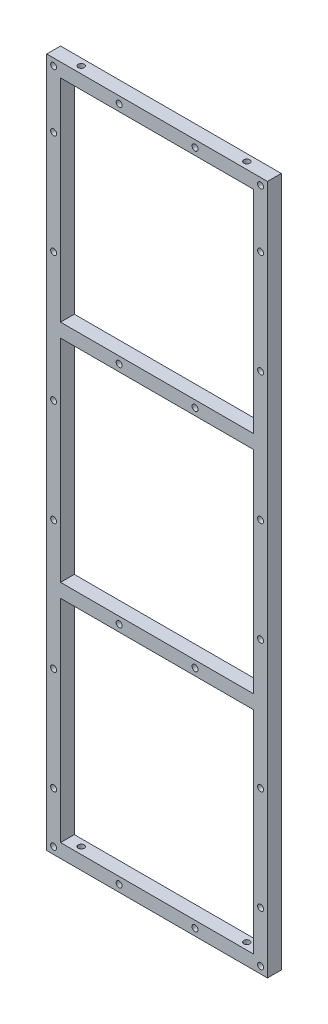
SolidWorks part; units mm, degrees
material "Alumina"
ref_plane "Front Plane" through (0, 0, 0) normal (0, 0, 1) x (1, 0, 0)
ref_plane "Top Plane" through (0, 0, 0) normal (0, 1, 0) x (1, 0, 0)
ref_plane "Right Plane" through (0, 0, 0) normal (1, 0, 0) x (0, 0, -1)
sketch "Sketch1" plane through (0, 0, 0) normal (0, 0, 1) x (1, 0, 0)
  line L0 (42, 144) -> (42, 52)
  line L9 (-48, -150) -> (48, -150)
  line L10 (-48, -150) -> (-48, 150)
  line L11 (-48, 150) -> (48, 150)
  line L12 (48, -150) -> (48, 150)
  line L14 (0, 0) -> (0, 46) construction
  line L15 (-42, -144) -> (42, -144)
  line L17 (-42, 144) -> (42, 144)
  line L19 (-42, 46) -> (-42, -46)
  line L20 (-42, -52) -> (-42, -144)
  line L21 (-42, 52) -> (42, 52)
  line L23 (-42, 46) -> (42, 46)
  line L25 (-42, -46) -> (42, -46)
  line L27 (-42, -52) -> (42, -52)
  line L33 (42, 46) -> (42, -46)
  line L34 (-42, 52) -> (-42, 144)
  line L36 (42, -52) -> (42, -144)
  dimension "D1" = 96
  dimension "D2" = 6
  dimension "D3" = 84
  dimension "D4" = 92
  dimension "D5" = 6
  dimension "D6" = 92
  dimension "D7" = 6
  dimension "D8" = 92
  dimension "D9" = 46
  dimension "D10" = 6
  dimension "D12" = 6
extrude "Boss-Extrude1" add sketch "Sketch1" along normal blind 6
sketch "Sketch2" plane through (0, 0, 6) normal (0, 0, 1) x (1, 0, 0)
  line L0 (-48, 150) -> (-42, 144) construction
  line L1 (42, 144) -> (48, 150) construction
  line L2 (42, -144) -> (48, -150) construction
  line L3 (-42, -144) -> (-48, -150) construction
  line L4 (-45, 147) -> (-45, 49) construction
  circle A0 centre (-45, 147) radius 1.3
  circle A1 centre (45, 147) radius 1.3
  circle A2 centre (-45, 49) radius 1.3
  circle A3 centre (45, 49) radius 1.3
  circle A4 centre (-45, -49) radius 1.3
  circle A5 centre (45, -49) radius 1.3
  circle A6 centre (-45, -147) radius 1.3
  circle A7 centre (45, -147) radius 1.3
  dimension "D1" = 2.6
  dimension "D5" = 2.6
  dimension "D3" = 98
  dimension "D2" = 4
extrude "Cut-Extrude1" cut sketch "Sketch2" against normal blind 6
sketch "Sketch3" plane through (0, 0, 6) normal (0, 0, 1) x (1, 0, 0)
  line L0 (48, 150) -> (-48, 150) construction
  line L1 (-48, 150) -> (-48, -150) construction
  line L2 (-45, 122) -> (45, 122) construction
  line L3 (-16.5, 147) -> (-16.5, 49) construction
  line L4 (-45, 122) -> (-45, 77) construction
  line L5 (-45, 122) -> (-45, 21) construction
  circle A0 centre (-45, 122) radius 1.3
  circle A12 centre (-16.5, 147) radius 1.3
  circle A19 centre (16.5, 147) radius 1.3
  circle A20 centre (-16.5, 49) radius 1.3
  circle A21 centre (16.5, 49) radius 1.3
  circle A22 centre (-16.5, -49) radius 1.3
  circle A23 centre (16.5, -49) radius 1.3
  circle A24 centre (-16.5, -147) radius 1.3
  circle A25 centre (16.5, -147) radius 1.3
  circle A26 centre (-45, 21) radius 1.3
  circle A27 centre (45, 122) radius 1.3
  circle A28 centre (45, 77) radius 1.3
  circle A29 centre (-45, 77) radius 1.3
  circle A30 centre (45, 21) radius 1.3
  circle A31 centre (45, -24) radius 1.3
  circle A32 centre (-45, -24) radius 1.3
  circle A33 centre (-45, -80) radius 1.3
  circle A34 centre (45, -80) radius 1.3
  circle A35 centre (45, -125) radius 1.3
  circle A36 centre (-45, -125) radius 1.3
  dimension "D1" = 28
  dimension "D6" = 2.6
  dimension "D3" = 2.6
  dimension "D8" = 3
  dimension "D9" = 33
  dimension "D10" = 31.5
  dimension "D12" = 2.6
  dimension "D13" = 45
  dimension "D14" = 3
  dimension "D2" = 90
  dimension "D7" = 3
  dimension "D11" = 98
  dimension "D16" = 101
  dimension "D4" = 2
  dimension "D5" = 2
  dimension "D15" = 3
sketch "Sketch4" plane through (0, 150, 0) normal (0, 1, 0) x (1, 0, 0)
  line L0 (48, 0) -> (-48, 0) construction
  line L1 (-48, -6) -> (-48, 0) construction
  line L2 (0, -3.3) -> (0, 3.3) construction
  circle A0 centre (-36, -3) radius 1.3
  circle A1 centre (36, -3) radius 1.3
  dimension "D1" = 3
  dimension "D3" = 2.6
  dimension "D2" = 12
extrude "Cut-Extrude5" cut sketch "Sketch4" against normal blind 10
mirror "Mirror1" about plane through (0, 0, 0) normal (0, 1, 0) of "Cut-Extrude5"
extrude "Cut-Extrude6" cut sketch "Sketch3" against normal blind 10
